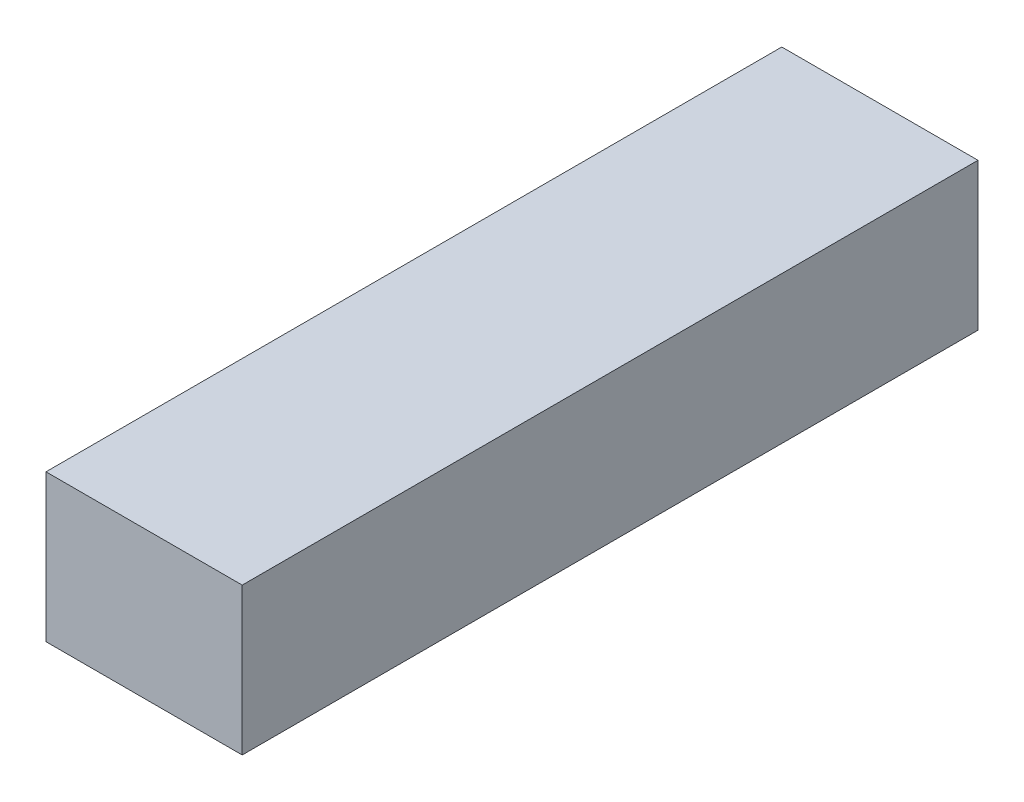
SolidWorks part; units mm, degrees
ref_plane "Front Plane" through (0, 0, 0) normal (0, 0, 1) x (1, 0, 0)
ref_plane "Top Plane" through (0, 0, 0) normal (0, 1, 0) x (1, 0, 0)
ref_plane "Right Plane" through (0, 0, 0) normal (1, 0, 0) x (0, 0, -1)
sketch "Sketch1" plane through (0, 0, 0) normal (0, 0, 1) x (1, 0, 0)
  line L0 (0, 0) -> (-8, 0)
  line L1 (-8, 0) -> (-8, 6)
  line L2 (-8, 6) -> (0, 6)
  line L3 (0, 6) -> (0, 0)
  dimension "D1" = 8
  dimension "D2" = 6
extrude "Boss-Extrude1" add sketch "Sketch1" along normal blind 30
